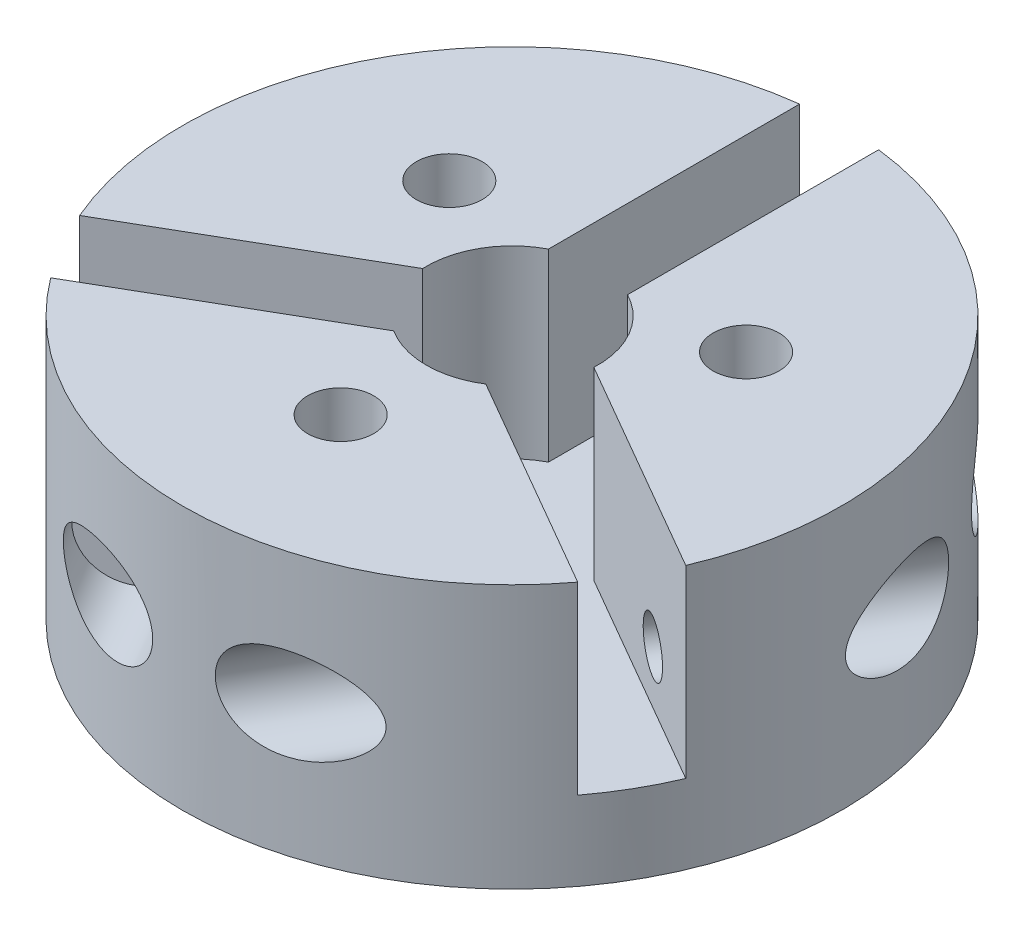
SolidWorks part; units mm, degrees
ref_plane "Front Plane" through (0, 0, 0) normal (0, 0, 1) x (1, 0, 0)
ref_plane "Top Plane" through (0, 0, 0) normal (0, 1, 0) x (1, 0, 0)
ref_plane "Right Plane" through (0, 0, 0) normal (1, 0, 0) x (0, 0, -1)
sketch "Sketch1" plane through (0, 0, 0) normal (0, 1, 0) x (1, 0, 0)
  circle A0 centre (0, 0) radius 125
  dimension "D1" = 250
extrude "Boss-Extrude1" add sketch "Sketch1" along normal mid plane 100
sketch "Sketch2" plane through (0, 50, 0) normal (0, 1, 0) x (1, 0, 0)
  line L0 (0, 0) -> (0, 135.2279) construction
  line L1 (0, 0) -> (172.9468, 0) construction
  line L2 (0, 0) -> (0, -65) construction
  circle A0 centre (0, 0) radius 65 construction
  circle A1 centre (0, -65) radius 12.5
  circle A2 centre (-56.2917, 32.5) radius 12.5
  circle A3 centre (56.2917, 32.5) radius 12.5
  dimension "D1" = 130
  dimension "D2" = 25
  dimension "D4" = 65
  dimension "D3" = 3
extrude "Cut-Extrude1" cut sketch "Sketch2" against normal blind 100
sketch "Sketch3" plane through (0, 50, 0) normal (0, 1, 0) x (1, 0, 0)
  line L0 (0, 0) -> (0, 134.5691) construction
  line L1 (0, 0) -> (187.112, 0) construction
  line L2 (-15, 124.0967) -> (-15, 28.8314)
  line L3 (15, 124.0967) -> (15, 28.8314)
  line L4 (99.9709, -75.0387) -> (17.4687, -27.4061)
  line L5 (114.9709, -49.058) -> (32.4687, -1.4253)
  line L6 (-114.9709, -49.058) -> (-32.4687, -1.4253)
  line L7 (-99.9709, -75.0387) -> (-17.4687, -27.4061)
  line L8 (0, 0) -> (15, 28.8314) construction
  arc A0 (-15, 28.8314) -> (-32.4687, -1.4253) centre (0, 0) ccw
  circle A1 centre (0, 0) radius 125 construction
  arc A2 (15, 124.0967) -> (-15, 124.0967) centre (0, 0) ccw
  arc A3 (99.9709, -75.0387) -> (114.9709, -49.058) centre (0, 0) ccw
  arc A4 (-114.9709, -49.058) -> (-99.9709, -75.0387) centre (0, 0) ccw
  arc A5 (-17.4687, -27.4061) -> (17.4687, -27.4061) centre (0, 0) ccw
  arc A6 (32.4687, -1.4253) -> (15, 28.8314) centre (0, 0) ccw
  point P3 (-239.0828, 21.1208)
  dimension "D1" = 65
  dimension "D4" = 3
  dimension "D2" = 30
  dimension "D3" = 15
extrude "Cut-Extrude2" cut sketch "Sketch3" against normal blind 70
sketch "Sketch4" plane through (0, 0, 0) normal (1, 0, 0) x (0, 0, -1)
  line L0 (0, 0) -> (156.0414, 0) construction
  circle A0 centre (90, 0) radius 10
  dimension "D1" = 20
  dimension "D2" = 90
extrude "Cut-Extrude3" cut sketch "Sketch4" against normal through all both and the other way through all
ref_plane "Plane1" through (55, 0, 0) normal (1, 0, 0) x (0, 0, -1)
sketch "Sketch6" plane through (55, 0, 0) normal (1, 0, 0) x (0, 0, -1)
  circle A0 centre (90, 0) radius 17.5
  dimension "D1" = 35
extrude "Cut-Extrude5" cut sketch "Sketch6" along normal blind 55 contours A0
mirror "Mirror1" about plane through (0, 0, 0) normal (1, 0, 0) of "Cut-Extrude5"
pattern_circular "CirPattern2" count 3 over 360 about axis through (0, 0, 0) along (0, 1, 0) of "Cut-Extrude5"
pattern_circular "CirPattern3" count 3 over 360 about axis through (0, -20, 0) along (0, 1, 0) of "Mirror1"
pattern_circular "CirPattern4" count 3 over 360 about axis through (0, -20, 0) along (0, 1, 0) of "Cut-Extrude3"
